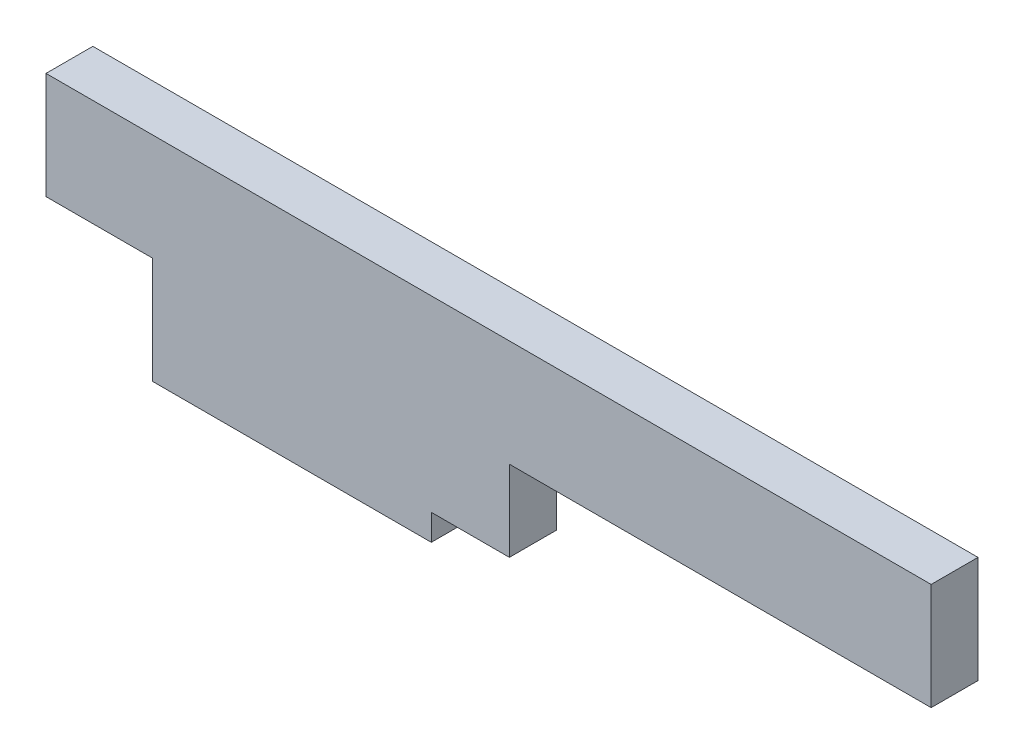
SolidWorks part; units mm, degrees
material "ABS"
ref_plane "Top Plane" through (0, 0, 0) normal (0, 0, 1) x (1, 0, 0)
ref_plane "Front Plane" through (0, 0, 0) normal (0, 1, 0) x (1, 0, 0)
ref_plane "Right Plane" through (0, 0, 0) normal (1, 0, 0) x (0, 0, -1)
sketch "Sketch1" plane through (0, 0, 0) normal (0, 0, 1) x (1, 0, 0)
  line L0 (-85, 18.5852) -> (85, 18.5852)
  line L1 (-85, 18.5852) -> (-85, -1.9148)
  line L2 (-85, -1.9148) -> (-64.5, -1.9148)
  line L3 (85, 18.5852) -> (85, -1.9148)
  line L4 (85, -1.9148) -> (4, -1.9148)
  line L5 (-64.5, -1.9148) -> (-64.5, -22.4148)
  line L6 (-64.5, -22.4148) -> (-11, -22.4148)
  line L7 (-11, -22.4148) -> (-11, -17.4148)
  line L8 (-11, -17.4148) -> (4, -17.4148)
  line L9 (4, -17.4148) -> (4, -1.9148)
  point P3 (0, 18.5852)
  dimension "D1" = 170
  dimension "D2" = 20.5
  dimension "D3" = 20.5
  dimension "D4" = 20.5
  dimension "D5" = 81
  dimension "D6" = 20.5
  dimension "D7" = 5
  dimension "D8" = 15
extrude "Boss-Extrude1" add sketch "Sketch1" along normal blind 9
